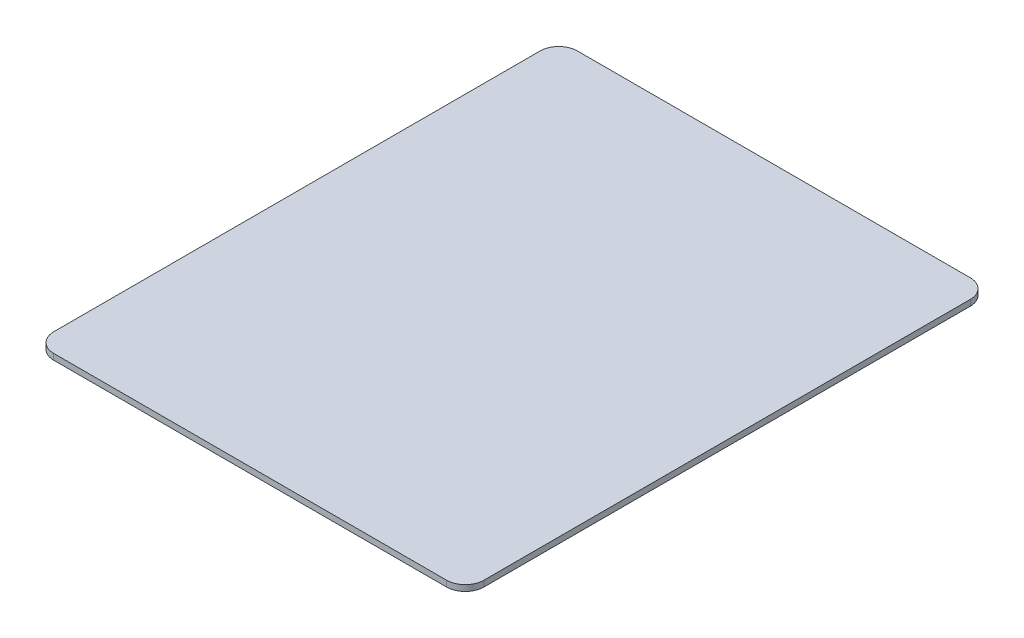
SolidWorks part; units mm, degrees
ref_plane "Front Plane" through (0, 0, 0) normal (0, 0, 1) x (1, 0, 0)
ref_plane "Top Plane" through (0, 0, 0) normal (0, 1, 0) x (1, 0, 0)
ref_plane "Right Plane" through (0, 0, 0) normal (1, 0, 0) x (0, 0, -1)
sketch "Sketch1" plane through (0, 0, 0) normal (0, 1, 0) x (1, 0, 0)
  line L1 (-115, -140) -> (115, -140)
  line L2 (-115, -140) -> (-115, 140)
  line L3 (-115, 140) -> (115, 140)
  line L4 (115, -140) -> (115, 140)
  line L5 (-115, -140) -> (115, 140) construction
  line L6 (-115, 140) -> (115, -140) construction
  point P0 (0, 0)
  dimension "D1" = 230
  dimension "D2" = 280
extrude "Boss-Extrude1" add sketch "Sketch1" along normal blind 3.175
fillet "Fillet1" radius 10 4 edges at (-115, 1.5875, -140) (115, 1.5875, -140) (115, 1.5875, 140) (-115, 1.5875, 140)
